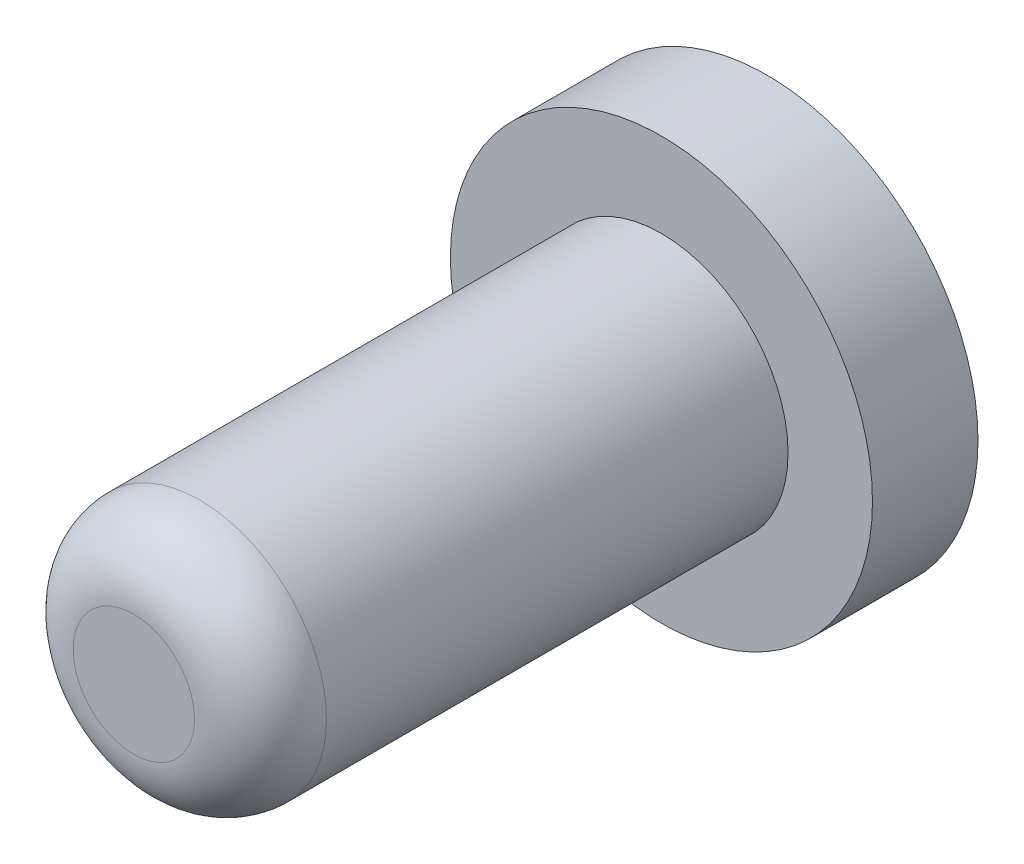
SolidWorks part; units mm, degrees
ref_plane "Top" through (0, 0, 0) normal (0, 0, 1) x (1, 0, 0)
ref_plane "Front" through (0, 0, 0) normal (0, 1, 0) x (1, 0, 0)
ref_plane "Right" through (0, 0, 0) normal (1, 0, 0) x (0, 0, -1)
sketch "Base Sketch" plane through (0, 0, 0) normal (0, 0, 1) x (1, 0, 0)
  circle A0 centre (0, 0) radius 4
  dimension "D1" = 8
extrude "Base Extrude" add sketch "Base Sketch" against normal blind 2
sketch "Sketch2" plane through (0, 0, 0) normal (0, 0, 1) x (1, 0, 0)
  circle A0 centre (0, 0) radius 2.4
  dimension "D1" = 4.8
extrude "Top Extrude" add sketch "Sketch2" along normal blind 10
fillet "Top Fillet" radius 1.25 1 edges at (2.4, 0, 10)
